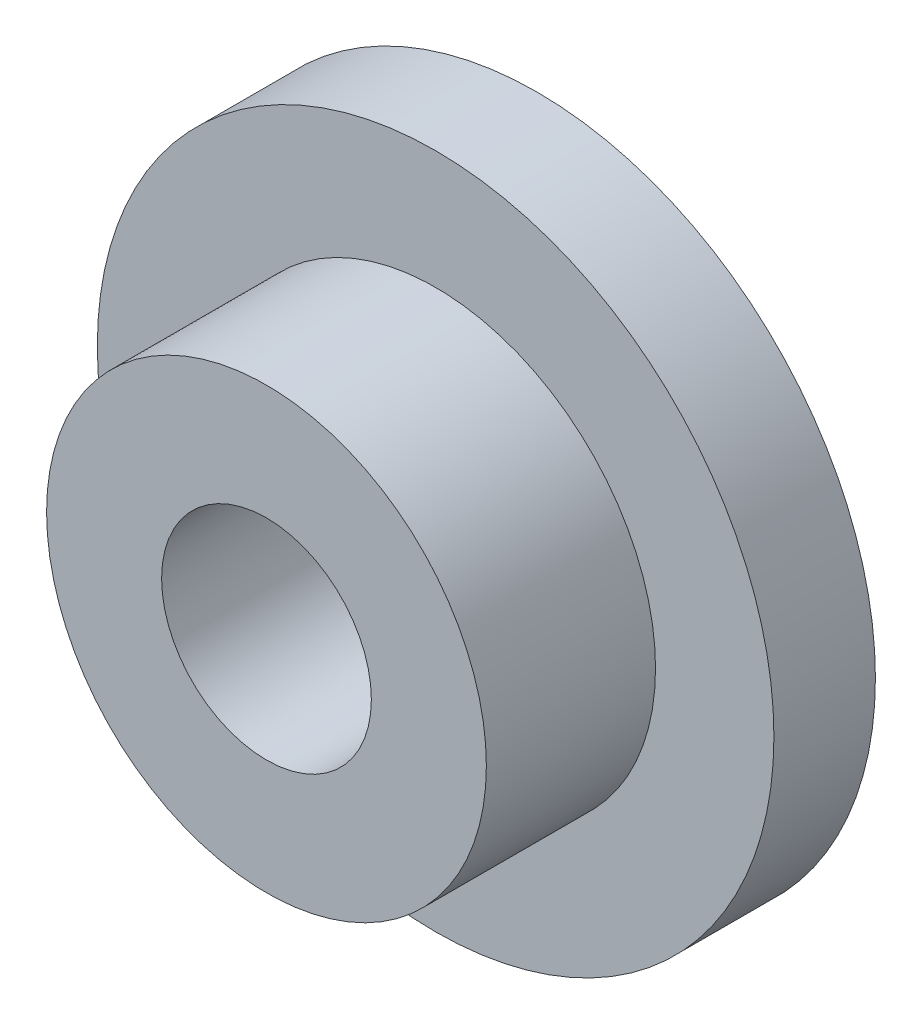
SolidWorks part; units mm, degrees
ref_plane "Alzado" through (0, 0, 0) normal (0, 0, 1) x (1, 0, 0)
ref_plane "Planta" through (0, 0, 0) normal (0, 1, 0) x (1, 0, 0)
ref_plane "Vista lateral" through (0, 0, 0) normal (1, 0, 0) x (0, 0, -1)
sketch "Croquis1" plane through (0, 0, 0) normal (0, 0, 1) x (1, 0, 0)
  circle A0 centre (0, 0) radius 5
  circle A2 centre (0, 0) radius 1.55
  dimension "D1" = 10
  dimension "D3" = 3.1
extrude "Saliente-Extruir1" add sketch "Croquis1" along normal blind 1.5
sketch "Croquis2" plane through (0, 0, 1.5) normal (0, 0, 1) x (1, 0, 0)
  circle A0 centre (0, 0) radius 1.55
  circle A1 centre (0, 0) radius 3.25
  dimension "D1" = 6.5
extrude "Saliente-Extruir2" add sketch "Croquis2" along normal blind 2.5
